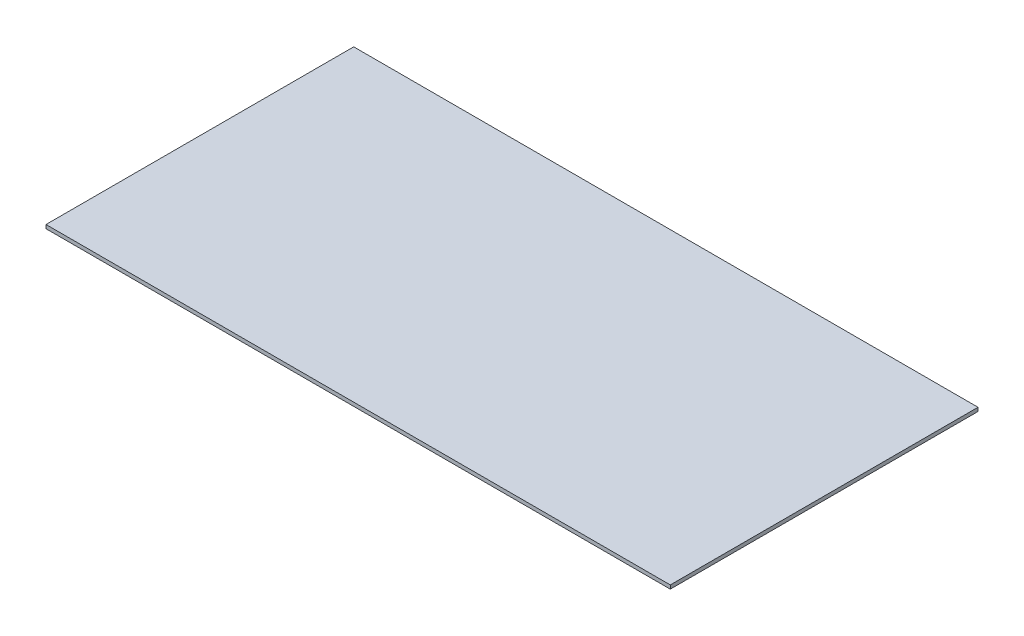
SolidWorks part; units mm, degrees
ref_plane "Front Plane" through (0, 0, 0) normal (0, 0, 1) x (1, 0, 0)
ref_plane "Top Plane" through (0, 0, 0) normal (0, 1, 0) x (1, 0, 0)
ref_plane "Right Plane" through (0, 0, 0) normal (1, 0, 0) x (0, 0, -1)
sketch "Sketch1" plane through (0, 0, 0) normal (0, 1, 0) x (1, 0, 0)
  line L1 (0, 0) -> (268.986, 0)
  line L2 (0, 0) -> (0, 132.588)
  line L3 (0, 132.588) -> (268.986, 132.588)
  line L4 (268.986, 0) -> (268.986, 132.588)
  dimension "D1" = 268.986
  dimension "D2" = 132.588
extrude "Boss-Extrude1" add sketch "Sketch1" along normal blind 1.5875
